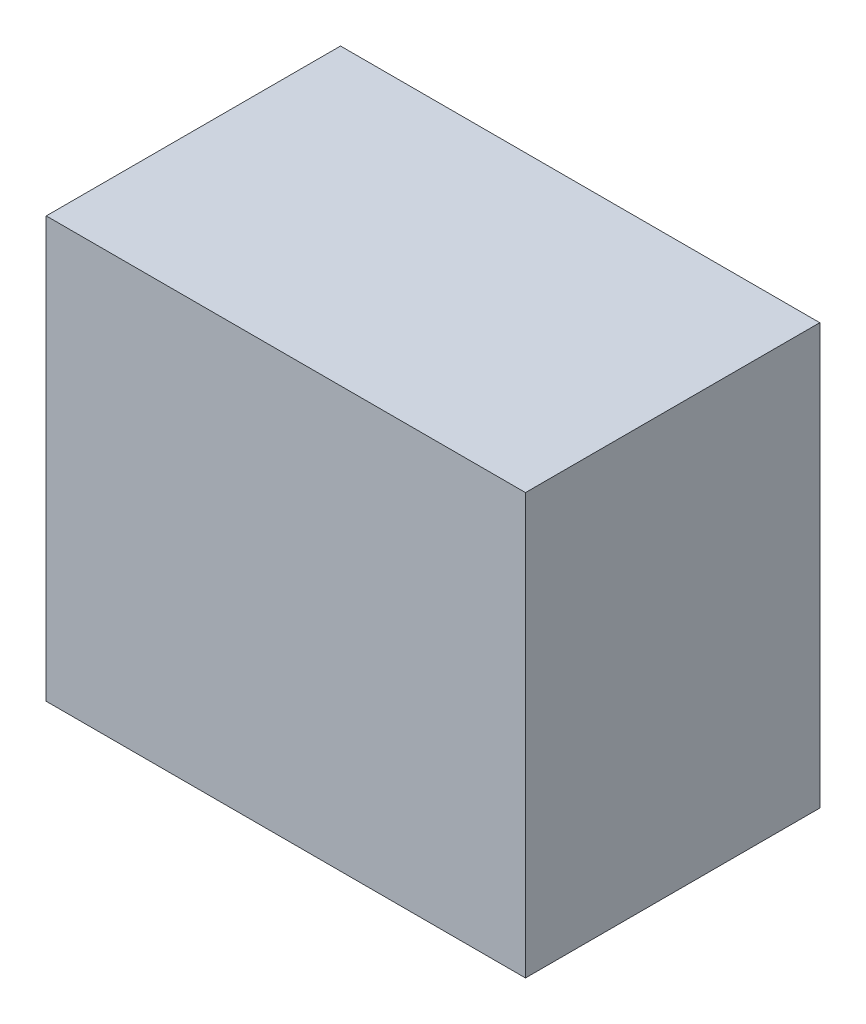
SolidWorks part; units mm, degrees
ref_plane "Front Plane" through (0, 0, 0) normal (0, 0, 1) x (1, 0, 0)
ref_plane "Top Plane" through (0, 0, 0) normal (0, 1, 0) x (1, 0, 0)
ref_plane "Right Plane" through (0, 0, 0) normal (1, 0, 0) x (0, 0, -1)
sketch "Sketch1" plane through (0, 0, 0) normal (0, 1, 0) x (1, 0, 0)
  line L1 (-28.5, 17.5) -> (28.5, 17.5)
  line L2 (-28.5, 17.5) -> (-28.5, -17.5)
  line L3 (-28.5, -17.5) -> (28.5, -17.5)
  line L4 (28.5, 17.5) -> (28.5, -17.5)
  line L5 (-28.5, 17.5) -> (28.5, -17.5) construction
  line L6 (-28.5, -17.5) -> (28.5, 17.5) construction
  point P0 (0, 0)
  dimension "D1" = 57
  dimension "D2" = 35
extrude "Boss-Extrude1" add sketch "Sketch1" along normal blind 50
ref_plane "Plane1" through (0, 1, 0) normal (0, 1, 0) x (1, 0, 0)
sketch "Sketch3" plane through (0, 1, 0) normal (0, 1, 0) x (1, 0, 0)
  line L1 (-27.5, 16.5) -> (27.5, 16.5)
  line L2 (-27.5, 16.5) -> (-27.5, -16.5)
  line L3 (-27.5, -16.5) -> (27.5, -16.5)
  line L4 (27.5, 16.5) -> (27.5, -16.5)
  line L5 (-27.5, 16.5) -> (27.5, -16.5) construction
  line L6 (-27.5, -16.5) -> (27.5, 16.5) construction
  point P0 (0, 0)
  dimension "D1" = 55
  dimension "D2" = 33
extrude "Cut-Extrude1" cut sketch "Sketch3" along normal blind 48
